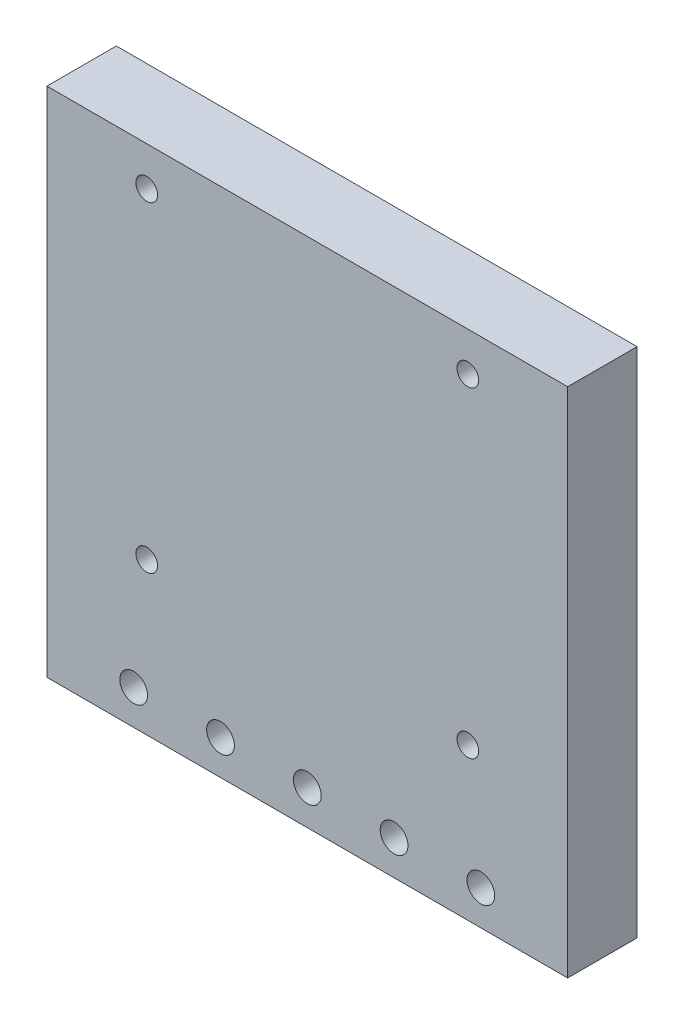
SolidWorks part; units mm, degrees
ref_plane "前视基准面" through (0, 0, 0) normal (0, 0, 1) x (1, 0, 0)
ref_plane "上视基准面" through (0, 0, 0) normal (0, 1, 0) x (1, 0, 0)
ref_plane "右视基准面" through (0, 0, 0) normal (1, 0, 0) x (0, 0, -1)
other "Configuration Table"
sketch "草图1" plane through (0, 0, 0) normal (0, 0, 1) x (1, 0, 0)
  line L1 (0, 0) -> (60, 0)
  line L2 (0, 0) -> (0, -59)
  line L3 (0, -59) -> (60, -59)
  line L4 (60, 0) -> (60, -59)
  dimension "D1" = 60
  dimension "D2" = 59
extrude "凸台-拉伸1" add sketch "草图1" along normal blind 8
sketch "草图2" plane through (0, 0, 8) normal (0, 0, 1) x (1, 0, 0)
  line L0 (11.5, -4.5) -> (48.5, -4.5) construction
  line L1 (48.5, -4.5) -> (48.5, -41.5) construction
  line L2 (48.5, -41.5) -> (11.5, -41.5) construction
  line L3 (11.5, -41.5) -> (11.5, -4.5) construction
  line L4 (60, 0) -> (0, 0) construction
  line L5 (60, -59) -> (60, 0) construction
  circle A0 centre (11.5, -4.5) radius 1.25
  circle A1 centre (48.5, -4.5) radius 1.25
  circle A2 centre (11.5, -41.5) radius 1.25
  circle A3 centre (48.5, -41.5) radius 1.25
  dimension "D1" = 2.5
  dimension "D2" = 37
  dimension "D3" = 4.5
  dimension "D4" = 11.5
extrude "切除-拉伸1" cut sketch "草图2" against normal blind 8
sketch "草图3" plane through (0, 0, 8) normal (0, 0, 1) x (1, 0, 0)
  line L0 (0, -51) -> (60, -51) construction
  line L1 (0, 0) -> (0, -59) construction
  line L2 (60, -59) -> (60, 0) construction
  line L3 (0, -59) -> (60, -59) construction
  line L4 (0, -55) -> (10, -55) construction
  line L5 (10, -55) -> (20, -55) construction
  line L6 (20, -55) -> (30, -55) construction
  line L7 (30, -55) -> (40, -55) construction
  line L8 (40, -55) -> (50, -55) construction
  line L9 (50, -55) -> (60, -55) construction
  circle A0 centre (10, -55) radius 1.6
  circle A1 centre (20, -55) radius 1.6
  circle A2 centre (30, -55) radius 1.6
  circle A3 centre (40, -55) radius 1.6
  circle A4 centre (50, -55) radius 1.6
  dimension "D4" = 3.2
  dimension "D1" = 8
  dimension "D2" = 4
  dimension "D3" = 10
extrude "切除-拉伸2" cut sketch "草图3" against normal through all
